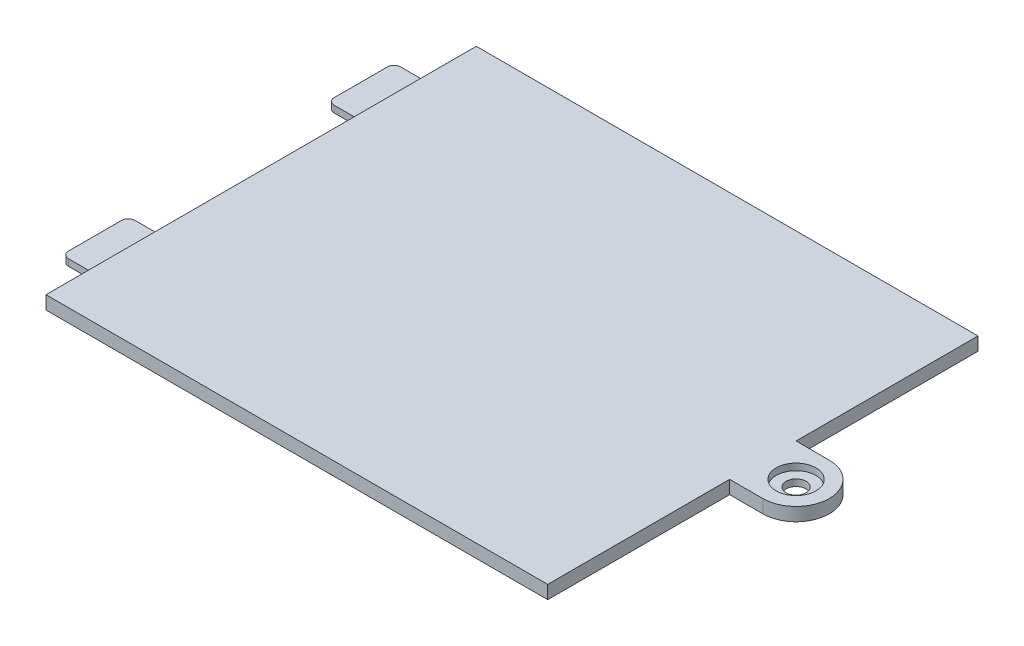
SolidWorks part; units mm, degrees
ref_plane "Front Plane" through (0, 0, 0) normal (0, 0, 1) x (1, 0, 0)
ref_plane "Top Plane" through (0, 0, 0) normal (0, 1, 0) x (1, 0, 0)
ref_plane "Right Plane" through (0, 0, 0) normal (1, 0, 0) x (0, 0, -1)
sketch "Sketch1" plane through (0, 0, 0) normal (0, 1, 0) x (1, 0, 0)
  line L1 (37.76, -32.385) -> (-37.76, -32.385)
  line L2 (37.76, -32.385) -> (37.76, 32.385)
  line L3 (37.76, 32.385) -> (-37.76, 32.385)
  line L4 (-37.76, -32.385) -> (-37.76, 32.385)
  line L5 (37.76, -32.385) -> (-37.76, 32.385) construction
  line L6 (37.76, 32.385) -> (-37.76, -32.385) construction
  point P0 (0, 0)
  dimension "D1" = 64.77
  dimension "D2" = 75.52
extrude "Boss-Extrude1" add sketch "Sketch1" along normal blind 2
sketch "Sketch2" plane through (0, 2, 0) normal (0, 1, 0) x (1, 0, 0)
  line L0 (37.76, 5) -> (42.76, 5)
  line L1 (37.76, -32.385) -> (37.76, 32.385) construction
  line L2 (42.76, -5) -> (37.76, -5)
  line L3 (37.76, -5) -> (37.76, 5)
  arc A0 (42.76, 5) -> (42.76, -5) centre (42.76, 0) cw
  dimension "D3" = 5
  dimension "D1" = 10
  dimension "D2" = 5
extrude "Boss-Extrude2" add sketch "Sketch2" against normal up to surface (2 mm away) up to face at (0, 0, 0)
sketch "Sketch3" plane through (-37.76, 0, 0) normal (-1, 0, 0) x (0, 0, 1)
  line L0 (-25, 0) -> (-25, 1)
  line L1 (-32.385, 0) -> (32.385, 0) construction
  line L2 (-25, 1) -> (-15, 1)
  line L3 (-15, 1) -> (-15, 0)
  line L4 (0, 0) -> (0, 6.904) construction
  line L5 (-25, 0) -> (-15, 0)
  line L6 (25, 0) -> (25, 1)
  line L7 (25, 1) -> (15, 1)
  line L8 (15, 1) -> (15, 0)
  line L9 (25, 0) -> (15, 0)
  dimension "D1" = 1
  dimension "D2" = 10
  dimension "D3" = 15
extrude "Boss-Extrude3" add sketch "Sketch3" along normal blind 5
sketch "Sketch7" plane through (0, 2, 0) normal (0, 1, 0) x (1, 0, 0)
  circle A1 centre (42.76, 0) radius 1.5
  dimension "D2" = 3
extrude "Cut-Extrude2" cut sketch "Sketch7" along direction (0, 1, 0) on the side against the normal up to surface (2 mm away)
sketch "Sketch9" plane through (0, 2, 0) normal (0, 1, 0) x (1, 0, 0)
  circle A0 centre (42.76, 0) radius 3
  circle A1 centre (42.76, 0) radius 1.5 construction
  circle A2 centre (42.76, 0) radius 1.5
  dimension "D1" = 6
extrude "Cut-Extrude4" cut sketch "Sketch9" against normal blind 1
fillet "Fillet1" radius 1 4 edges at (-42.76, 0.5, 25) (-42.76, 0.5, 15) (-42.76, 0.5, -15) (-42.76, 0.5, -25)
